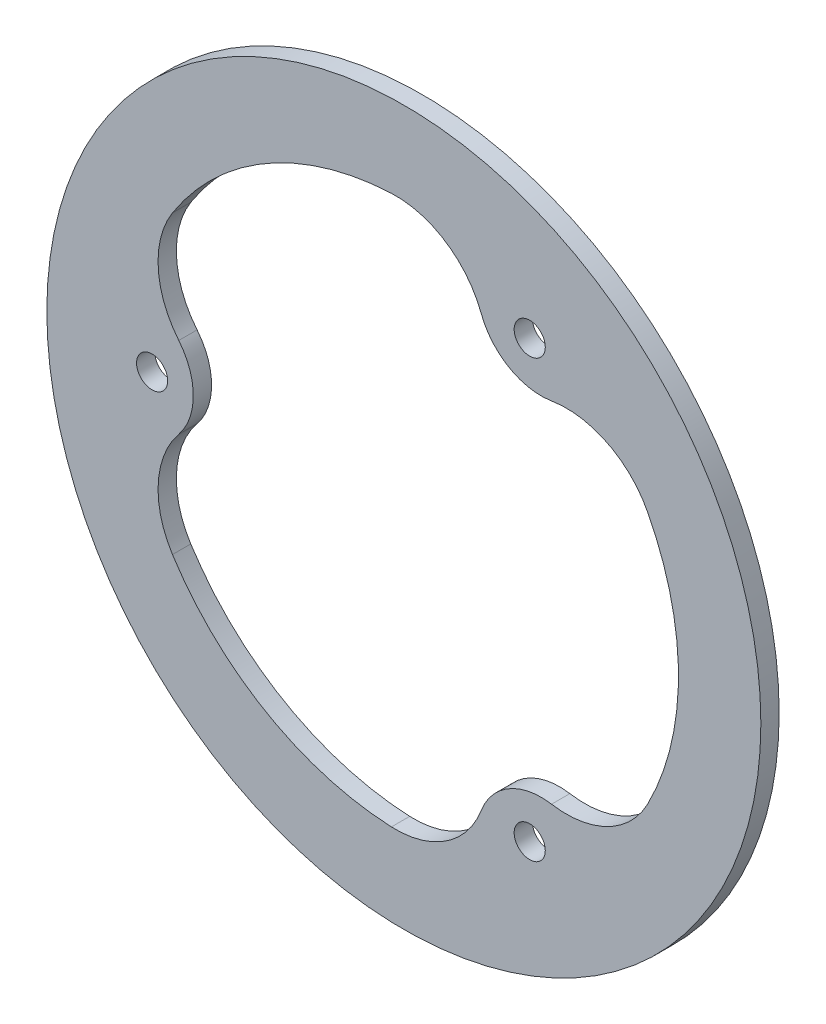
SolidWorks part; units mm, degrees
ref_plane "Спереди" through (0, 0, 0) normal (0, 0, 1) x (1, 0, 0)
ref_plane "Сверху" through (0, 0, 0) normal (0, 1, 0) x (1, 0, 0)
ref_plane "Справа" through (0, 0, 0) normal (1, 0, 0) x (0, 0, -1)
sketch "Эскиз1" plane through (0, 0, 0) normal (0, 0, 1) x (1, 0, 0)
  line L0 (-47.2647, 0) -> (45.7267, 0) construction
  line L1 (0, 0) -> (25.3131, 43.8436) construction
  line L2 (0, 0) -> (23.2677, -40.3008) construction
  circle A0 centre (0, 0) radius 39
  arc A1 (20.6124, -21.7974) -> (20.6124, 21.7974) centre (0, 0) ccw
  circle A2 centre (0, 0) radius 27.5 construction
  circle A3 centre (0, 0) radius 23 construction
  arc A4 (-29.1833, -6.9522) -> (-29.1833, 6.9522) centre (-30, 0) ccw
  arc A5 (20.6124, -21.7974) -> (8.5709, -28.7496) centre (15, -25.9808) ccw
  arc A6 (8.5709, 28.7496) -> (20.6124, 21.7974) centre (15, 25.9808) ccw
  arc A7 (-29.1833, -6.9522) -> (8.5709, -28.7496) centre (0, 0) ccw
  arc A8 (8.5709, 28.7496) -> (-29.1833, 6.9522) centre (0, 0) ccw
  dimension "D1" = 78
  dimension "D2" = 60
  dimension "D3" = 55
  dimension "D4" = 46
  dimension "D5" = 60
  dimension "D6" = 60
extrude "Бобышка-Вытянуть1" add sketch "Эскиз1" along normal blind 2
fillet "Скругление1" radius 10 6 edges at (20.6124, -21.7974, 1) (8.5709, -28.7496, 1) (-29.1833, -6.9522, 1) (-29.1833, 6.9522, 1) (20.6124, 21.7974, 1) (8.5709, 28.7496, 1)
hole_wizard "Отверстие с зазором M31" positions "Эскиз3" profile "Эскиз2" hole size "M3" standard "Ansi Metric" end condition through all
sketch "Эскиз3" plane through (0, 0, 2) normal (0, 0, 1) x (1, 0, 0)
  line L0 (0, 0) -> (25.3131, 43.8436) construction
  line L1 (-47.2647, 0) -> (45.7267, 0) construction
  line L2 (0, 0) -> (23.2677, -40.3008) construction
  circle A0 centre (0, 0) radius 27.5 construction
  point P0 (13.75, 23.8157)
  point P6 (-27.5, 0)
  point P10 (13.75, -23.8157)
sketch "Эскиз2" plane through (13.75, 23.8157, 2) normal (1, 0, 0) x (0, -1, 0)
  line L0 (0, 0) -> (0, 2)
  line L1 (0, 2) -> (1.7, 2)
  line L2 (1.7, 2) -> (1.7, 0)
  line L5 (1.7, 0) -> (0, 0)
  line L11 (0, -6.35) -> (0, 107.95) construction
  dimension "Диаметр сквозного отверстия" = 3.4
  dimension "Глубина сквозного отверстия" = 2
sketch "Эскиз4" plane through (0, 0, 2) normal (0, 0, 1) x (1, 0, 0)
  line L0 (-39, -15.5682) -> (-39, -39) construction
  line L1 (-39, -39) -> (-24.8169, -39) construction
  circle A0 centre (0, 0) radius 39 construction
